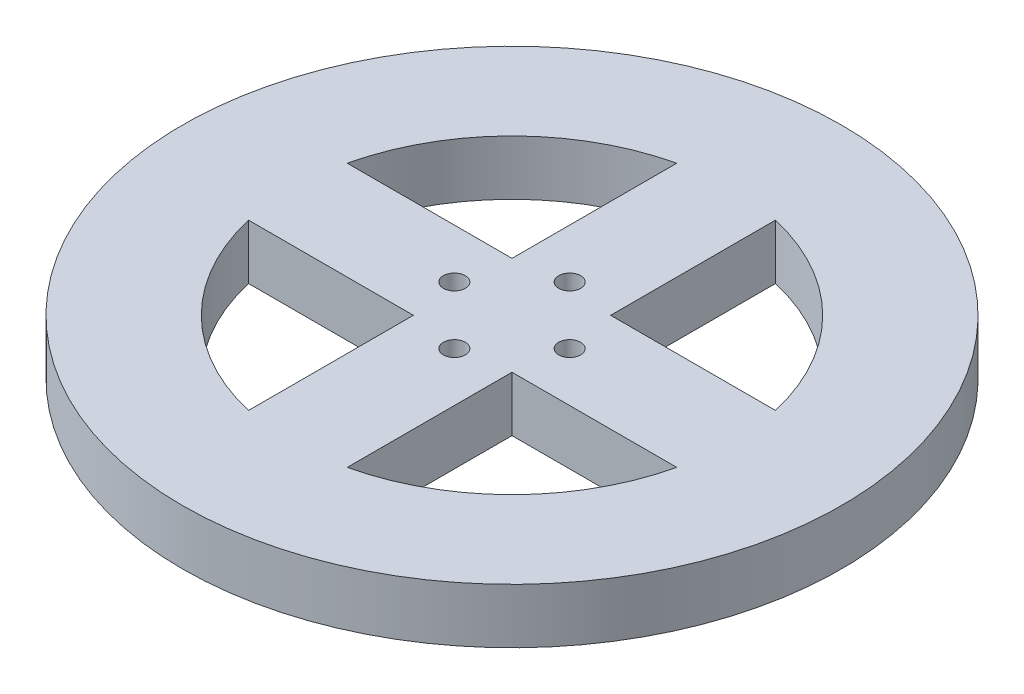
SolidWorks part; units mm, degrees
ref_plane "Front Plane" through (0, 0, 0) normal (0, 0, 1) x (1, 0, 0)
ref_plane "Top Plane" through (0, 0, 0) normal (0, 1, 0) x (1, 0, 0)
ref_plane "Right Plane" through (0, 0, 0) normal (1, 0, 0) x (0, 0, -1)
sketch "Sketch2" plane through (0, 0, 0) normal (0, 1, 0) x (1, 0, 0)
  line L0 (-8.9792, -38.9792) -> (-8.9792, -8.9792)
  line L1 (-8.9792, -8.9792) -> (-38.9792, -8.9792)
  line L2 (-8.9792, 8.9792) -> (-8.9792, 38.9792)
  line L3 (-38.9792, 8.9792) -> (-8.9792, 8.9792)
  line L4 (8.9792, 8.9792) -> (38.9792, 8.9792)
  line L5 (8.9792, 38.9792) -> (8.9792, 8.9792)
  line L6 (8.9792, -8.9792) -> (8.9792, -38.9792)
  line L7 (38.9792, -8.9792) -> (8.9792, -8.9792)
  line L8 (-8.9792, -8.9792) -> (8.9792, 8.9792) construction
  circle A0 centre (0, 0) radius 60
  arc A2 (-8.9792, 38.9792) -> (-38.9792, 8.9792) centre (0, 0) ccw
  arc A3 (-38.9792, -8.9792) -> (-8.9792, -38.9792) centre (0, 0) ccw
  arc A4 (38.9792, 8.9792) -> (8.9792, 38.9792) centre (0, 0) ccw
  arc A5 (8.9792, -38.9792) -> (38.9792, -8.9792) centre (0, 0) ccw
  point P6 (16.8935, 16.8935)
  point P8 (0, 0)
  point P9 (0, 0)
  dimension "D1" = 120
  dimension "D2" = 30
  dimension "D3" = 80
  dimension "D4" = 4
extrude "Boss-Extrude2" add sketch "Sketch2" along normal blind 10
sketch "Sketch3" plane through (0, 0, 0) normal (0, -1, 0) x (1, 0, 0)
  line L0 (0, 0) -> (-10.5, 0) construction
  line L1 (0, 0) -> (0, 10.5) construction
  line L2 (0, 0) -> (10.5, 0) construction
  line L3 (0, 0) -> (0, -10.5) construction
  circle A0 centre (-10.5, 0) radius 2
  circle A1 centre (0, 10.5) radius 2
  circle A2 centre (10.5, 0) radius 2
  circle A3 centre (0, -10.5) radius 2
  dimension "D2" = 4
  dimension "D1" = 10.5
  dimension "D3" = 4
extrude "Cut-Extrude1" cut sketch "Sketch3" against normal through all
sketch "Sketch39" plane through (0, 10, 0) normal (0, 1, 0) x (1, 0, 0)
  line L0 (0, 0) -> (25, 0) construction
  line L1 (0, 0) -> (0, -25) construction
  line L2 (0, 0) -> (-25, 0) construction
  line L3 (0, 0) -> (0, 25) construction
  circle A0 centre (25, 0) radius 2
  circle A1 centre (0, -25) radius 2
  circle A2 centre (-25, 0) radius 2
  circle A3 centre (0, 25) radius 2
  dimension "D1" = 4
  dimension "D2" = 25
  dimension "D3" = 4
extrude "Cut-Extrude4" [suppressed] cut sketch "Sketch39" against normal through all and the other way through all
